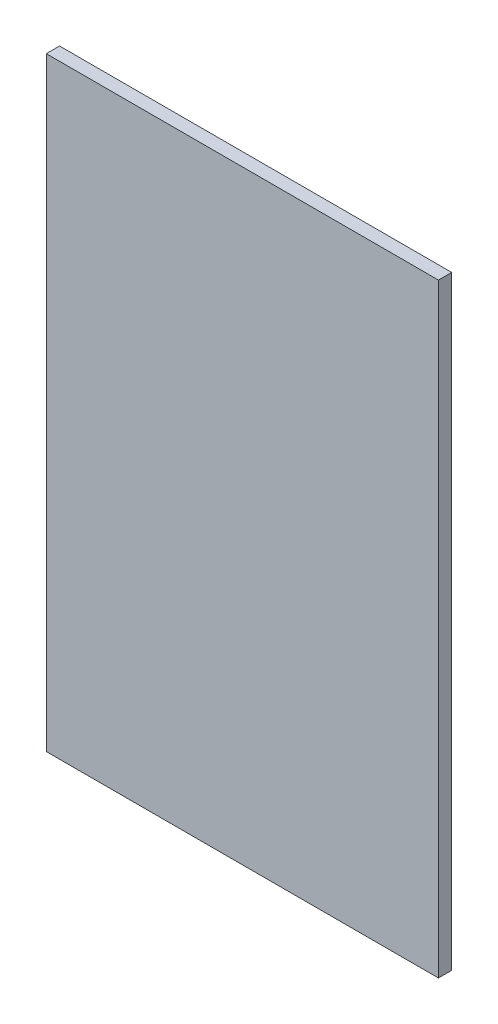
SolidWorks part; units mm, degrees
material "Pine"
ref_plane "Front Plane" through (0, 0, 0) normal (0, 0, 1) x (1, 0, 0)
ref_plane "Top Plane" through (0, 0, 0) normal (0, 1, 0) x (1, 0, 0)
ref_plane "Right Plane" through (0, 0, 0) normal (1, 0, 0) x (0, 0, -1)
sketch "Sketch1" plane through (0, 0, 0) normal (0, 0, 1) x (1, 0, 0)
  line L1 (-266, 410) -> (266, 410)
  line L2 (-266, 410) -> (-266, -410)
  line L3 (-266, -410) -> (266, -410)
  line L4 (266, 410) -> (266, -410)
  line L5 (-266, 410) -> (266, -410) construction
  line L6 (-266, -410) -> (266, 410) construction
  point P0 (0, 0)
  dimension "D1" = 532
  dimension "D2" = 820
extrude "Boss-Extrude1" add sketch "Sketch1" along normal blind 18
